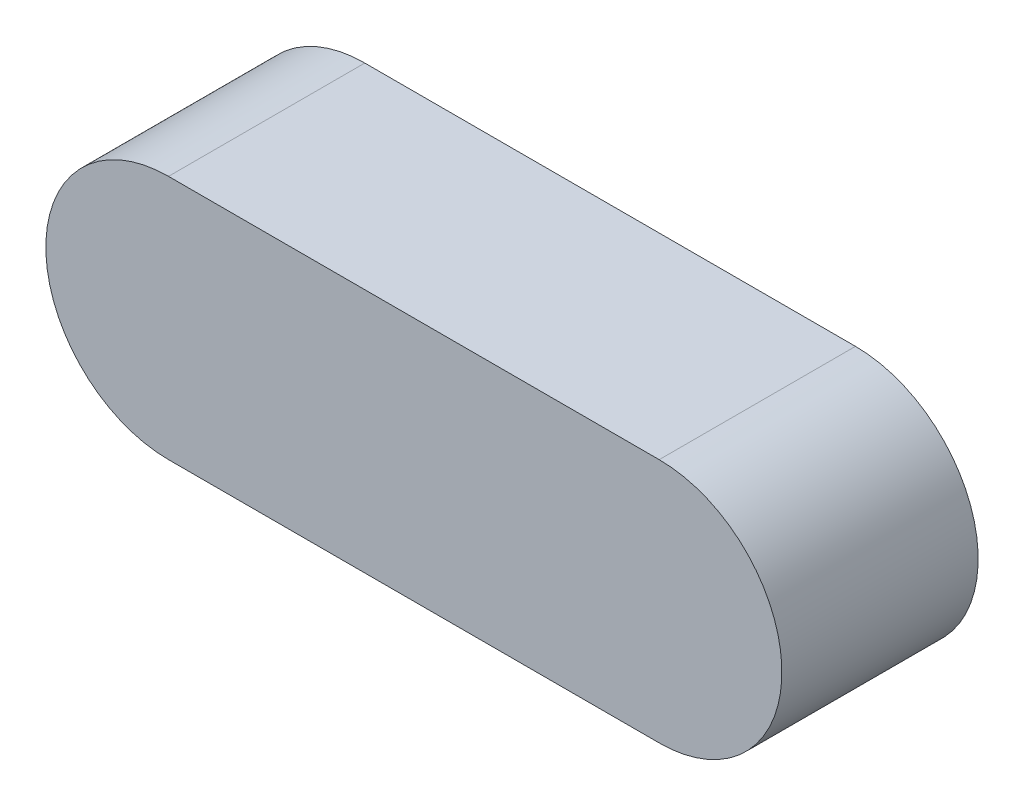
SolidWorks part; units mm, degrees
ref_plane "Piano frontale" through (0, 0, 0) normal (0, 0, 1) x (1, 0, 0)
ref_plane "Piano superiore" through (0, 0, 0) normal (0, 1, 0) x (1, 0, 0)
ref_plane "Piano destro" through (0, 0, 0) normal (1, 0, 0) x (0, 0, -1)
sketch "Schizzo1" plane through (0, 0, 0) normal (0, 0, 1) x (1, 0, 0)
  line L0 (0, 0) -> (20, 0) construction
  line L1 (0, 5) -> (20, 5)
  line L2 (0, -5) -> (20, -5)
  arc A2 (0, 5) -> (0, -5) centre (0, 0) ccw
  arc A3 (20, -5) -> (20, 5) centre (20, 0) ccw
  dimension "D1" = 10
  dimension "D2" = 10
  dimension "17" = 20
extrude "Estrusione-Estrusione1" add sketch "Schizzo1" along normal blind 8
